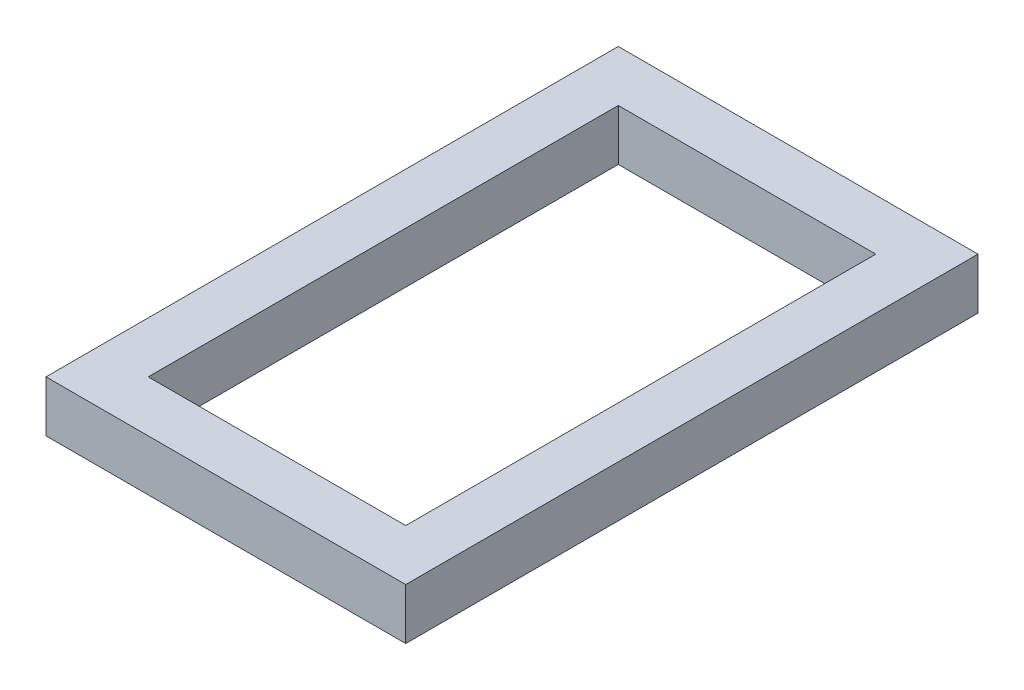
SolidWorks part; units mm, degrees
ref_plane "Front Plane" through (0, 0, 0) normal (0, 0, 1) x (1, 0, 0)
ref_plane "Top Plane" through (0, 0, 0) normal (0, 1, 0) x (1, 0, 0)
ref_plane "Right Plane" through (0, 0, 0) normal (1, 0, 0) x (0, 0, -1)
sketch "Sketch1" plane through (0, 0, 0) normal (0, 1, 0) x (1, 0, 0)
  line L0 (-8.8, 14) -> (8.8, 14)
  line L1 (-6.3, -11.5) -> (6.3, -11.5)
  line L2 (-6.3, -11.5) -> (-6.3, 11.5)
  line L3 (-6.3, 11.5) -> (6.3, 11.5)
  line L4 (6.3, -11.5) -> (6.3, 11.5)
  line L5 (-6.3, -11.5) -> (6.3, 11.5) construction
  line L6 (-6.3, 11.5) -> (6.3, -11.5) construction
  line L7 (8.8, -14) -> (8.8, 14)
  line L8 (-8.8, -14) -> (8.8, -14)
  line L9 (-8.8, -14) -> (-8.8, 14)
  point P0 (0, 0)
  dimension "D1" = 23
  dimension "D2" = 12.6
  dimension "D3" = 2.5
extrude "Boss-Extrude1" add sketch "Sketch1" along normal blind 2.5
